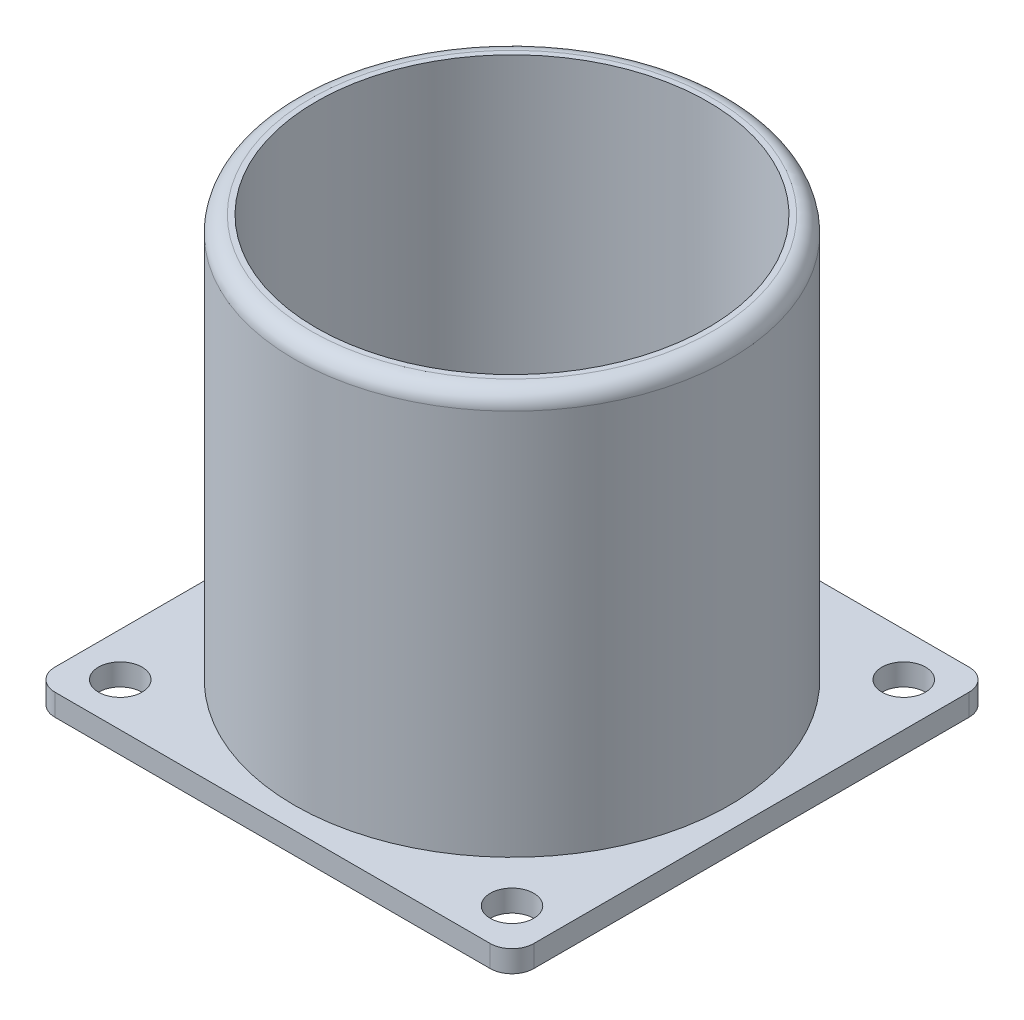
SolidWorks part; units mm, degrees
ref_plane "Plano frontal" through (0, 0, 0) normal (0, 0, 1) x (1, 0, 0)
ref_plane "Plano superior" through (0, 0, 0) normal (0, 1, 0) x (1, 0, 0)
ref_plane "Plano direito" through (0, 0, 0) normal (1, 0, 0) x (0, 0, -1)
sketch "Esboço1" plane through (0, 0, 0) normal (0, 1, 0) x (1, 0, 0)
  line L0 (0, 0) -> (0, 18) construction
  line L1 (-22, -22) -> (22, -22)
  line L2 (-22, -22) -> (-22, 22)
  line L3 (-22, 22) -> (22, 22)
  line L4 (22, -22) -> (22, 22)
  line L5 (-22, -22) -> (22, 22) construction
  line L6 (-22, 22) -> (22, -22) construction
  line L7 (-22, -18) -> (-18, -18) construction
  line L8 (-22, -18) -> (-22, -22) construction
  line L9 (-22, -22) -> (-18, -22) construction
  line L10 (-18, -18) -> (-18, -22) construction
  line L11 (-22, -18) -> (-18, -22) construction
  line L12 (-22, -22) -> (-18, -18) construction
  line L13 (0, 0) -> (8.3253, 0) construction
  line L14 (0.75, -17.9844) -> (0.75, 18)
  line L15 (-18, -18) -> (-16, -18) construction
  line L16 (-18, -18) -> (-18, -16) construction
  line L17 (-18, 18) -> (-6.75, 18) construction
  line L18 (18, -18) -> (18, 18) construction
  line L19 (-18, -18) -> (18, 18) construction
  line L20 (-18, 18) -> (18, -18) construction
  line L21 (-0.75, -17.9844) -> (-0.75, 18)
  line L22 (-0.75, 0) -> (-0.75, 22) construction
  line L23 (0.75, 0) -> (0.75, 22) construction
  line L24 (0.75, 18) -> (0.75, 22) construction
  line L25 (0, 17.7309) -> (0, 22) construction
  line L26 (0, 0) -> (0, 22) construction
  line L27 (-0.75, 18) -> (-0.75, 22) construction
  line L28 (0.75, -17.9844) -> (0.75, 18)
  line L29 (2.25, -17.9844) -> (2.25, 18)
  line L30 (2.25, -17.9844) -> (2.25, 18)
  line L31 (3.75, -17.9844) -> (3.75, 18)
  line L32 (3.75, -17.9844) -> (3.75, 18)
  line L33 (5.25, -17.9844) -> (5.25, 18)
  line L34 (5.25, -17.9844) -> (5.25, 18)
  line L35 (6.75, -17.9844) -> (6.75, 18)
  line L36 (6.75, -17.9844) -> (6.75, 18)
  line L37 (8.25, -17.9844) -> (8.25, 18)
  line L38 (8.25, -17.9844) -> (8.25, 18)
  line L39 (9.75, -17.9844) -> (9.75, 18)
  line L40 (9.75, -17.9844) -> (9.75, 18)
  line L41 (11.25, -17.9844) -> (11.25, 18)
  line L42 (11.25, -17.9844) -> (11.25, 18)
  line L43 (12.75, -17.9844) -> (12.75, 18)
  line L44 (12.75, -17.9844) -> (12.75, 18)
  line L45 (14.25, -17.9844) -> (14.25, 18)
  line L46 (14.25, -17.9844) -> (14.25, 18)
  line L47 (15.75, -17.9844) -> (15.75, 18)
  line L48 (15.75, -17.9844) -> (15.75, 18)
  line L49 (17.25, -17.9844) -> (17.25, 18)
  line L50 (-0.75, -17.9844) -> (0.75, -17.9844) construction
  line L51 (-0.75, 18) -> (0, 18) construction
  line L52 (0.75, 18) -> (2.25, 18) construction
  line L53 (0, 18) -> (0.75, 18) construction
  line L54 (-16, -18) -> (0, -18) construction
  line L55 (16, -18) -> (18, -18) construction
  line L56 (0, -18) -> (16, -18) construction
  line L57 (2.25, 18) -> (3.75, 18) construction
  line L58 (3.75, 18) -> (5.25, 18) construction
  line L59 (5.25, 18) -> (6.75, 18) construction
  line L60 (6.75, 18) -> (18, 18) construction
  line L61 (-17.25, -17.9844) -> (-17.25, 18)
  line L62 (-15.75, -17.9844) -> (-15.75, 18)
  line L63 (-14.25, -17.9844) -> (-14.25, 18)
  line L64 (-12.75, -17.9844) -> (-12.75, 18)
  line L65 (-11.25, -17.9844) -> (-11.25, 18)
  line L66 (-9.75, -17.9844) -> (-9.75, 18)
  line L67 (-8.25, -17.9844) -> (-8.25, 18)
  line L68 (-6.75, -17.9844) -> (-6.75, 18)
  line L69 (-5.25, -17.9844) -> (-5.25, 18)
  line L70 (-3.75, -17.9844) -> (-3.75, 18)
  line L71 (-2.25, -17.9844) -> (-2.25, 18)
  line L72 (-3.75, 18) -> (-2.25, 18) construction
  line L73 (-2.25, 18) -> (-0.75, 18) construction
  line L74 (-6.75, 18) -> (-5.25, 18) construction
  line L75 (-5.25, 18) -> (-3.75, 18) construction
  line L76 (-18, 0) -> (-18, 16) construction
  line L77 (-18, 16) -> (-18, 18) construction
  line L78 (-18, -16) -> (-18, 0) construction
  arc A0 (-0.75, 17.9844) -> (-2.25, 17.8588) centre (0, 0) ccw
  circle A1 centre (-18, -18) radius 2
  circle A2 centre (18, -18) radius 2
  circle A3 centre (18, 18) radius 2
  circle A4 centre (-18, 18) radius 2
  arc A5 (0, 18) -> (-0.75, 17.9844) centre (0, 0) ccw construction
  arc A6 (0.75, 17.9844) -> (0, 18) centre (0, 0) ccw construction
  arc A7 (-0.75, -17.9844) -> (0, -18) centre (0, 0) ccw construction
  arc A8 (0, -18) -> (2.25, -17.8588) centre (0, 0) ccw
  arc A9 (2.25, -17.8588) -> (3.75, -17.605) centre (0, 0) ccw construction
  arc A10 (3.75, -17.605) -> (5.25, -17.2174) centre (0, 0) ccw
  arc A11 (3.75, 17.605) -> (2.25, 17.8588) centre (0, 0) ccw construction
  arc A12 (2.25, 17.8588) -> (0.75, 17.9844) centre (0, 0) ccw
  arc A13 (6.75, 16.6864) -> (5.25, 17.2174) centre (0, 0) ccw construction
  arc A14 (5.25, 17.2174) -> (3.75, 17.605) centre (0, 0) ccw
  arc A15 (5.25, -17.2174) -> (6.75, -16.6864) centre (0, 0) ccw construction
  arc A16 (6.75, -16.6864) -> (8.25, -15.998) centre (0, 0) ccw
  arc A17 (8.25, -15.998) -> (9.75, -15.1307) centre (0, 0) ccw construction
  arc A18 (9.75, -15.1307) -> (11.25, -14.0512) centre (0, 0) ccw
  arc A19 (9.75, 15.1307) -> (8.25, 15.998) centre (0, 0) ccw construction
  arc A20 (8.25, 15.998) -> (6.75, 16.6864) centre (0, 0) ccw
  arc A21 (12.7279, 12.7279) -> (11.25, 14.0512) centre (0, 0) ccw construction
  arc A22 (11.25, 14.0512) -> (9.75, 15.1307) centre (0, 0) ccw
  arc A23 (11.25, -14.0512) -> (12.7279, -12.7279) centre (0, 0) ccw construction
  arc A24 (12.7279, -12.7279) -> (14.25, -10.9972) centre (0, 0) ccw
  arc A25 (14.25, -10.9972) -> (15.75, -8.7142) centre (0, 0) ccw construction
  arc A26 (15.75, -8.7142) -> (17.25, -5.1417) centre (0, 0) ccw
  arc A27 (15.75, 8.7142) -> (14.25, 10.9972) centre (0, 0) ccw construction
  arc A28 (14.25, 10.9972) -> (12.7279, 12.7279) centre (0, 0) ccw
  arc A29 (18, 0) -> (17.25, 5.1417) centre (0, 0) ccw construction
  arc A30 (17.25, 5.1417) -> (15.75, 8.7142) centre (0, 0) ccw
  arc A31 (17.25, -5.1417) -> (18, 0) centre (0, 0) ccw construction
  arc A32 (-2.25, 17.8588) -> (-3.75, 17.605) centre (0, 0) ccw construction
  arc A33 (-3.75, 17.605) -> (-5.25, 17.2174) centre (0, 0) ccw
  arc A34 (-3.75, -17.605) -> (-2.25, -17.8588) centre (0, 0) ccw construction
  arc A35 (-2.25, -17.8588) -> (-0.75, -17.9844) centre (0, 0) ccw
  arc A36 (-6.75, -16.6864) -> (-5.25, -17.2174) centre (0, 0) ccw construction
  arc A37 (-5.25, -17.2174) -> (-3.75, -17.605) centre (0, 0) ccw
  arc A38 (-5.25, 17.2174) -> (-6.75, 16.6864) centre (0, 0) ccw construction
  arc A39 (-6.75, 16.6864) -> (-8.25, 15.998) centre (0, 0) ccw
  arc A40 (-8.25, 15.998) -> (-9.75, 15.1307) centre (0, 0) ccw construction
  arc A41 (-9.75, 15.1307) -> (-11.25, 14.0512) centre (0, 0) ccw
  arc A42 (-9.75, -15.1307) -> (-8.25, -15.998) centre (0, 0) ccw construction
  arc A43 (-8.25, -15.998) -> (-6.75, -16.6864) centre (0, 0) ccw
  arc A44 (-12.7279, -12.7279) -> (-11.25, -14.0512) centre (0, 0) ccw construction
  arc A45 (-11.25, -14.0512) -> (-9.75, -15.1307) centre (0, 0) ccw
  arc A46 (-11.25, 14.0512) -> (-12.7279, 12.7279) centre (0, 0) ccw construction
  arc A47 (-12.7279, 12.7279) -> (-14.25, 10.9972) centre (0, 0) ccw
  arc A48 (-14.25, 10.9972) -> (-15.75, 8.7142) centre (0, 0) ccw construction
  arc A49 (-15.75, 8.7142) -> (-17.25, 5.1417) centre (0, 0) ccw
  arc A50 (-15.75, -8.7142) -> (-14.25, -10.9972) centre (0, 0) ccw construction
  arc A51 (-14.25, -10.9972) -> (-12.7279, -12.7279) centre (0, 0) ccw
  arc A52 (-17.25, 5.1417) -> (-18, 0) centre (0, 0) ccw construction
  arc A53 (-17.25, -5.1417) -> (-15.75, -8.7142) centre (0, 0) ccw
  arc A54 (-18, 0) -> (-17.25, -5.1417) centre (0, 0) ccw construction
  point P7 (-20, -20)
  dimension "D1" = 36
  dimension "D4" = 4
  dimension "D2" = 44
  dimension "D3" = 4
  dimension "D8" = 1.5
  dimension "D5" = 0.75
  dimension "D6" = 0.75
  dimension "D7" = 12
extrude "Ressalto-extrusão1" add sketch "Esboço1" along normal blind 2
ref_plane "Plano1" through (0, 2, 0) normal (0, 1, 0) x (1, 0, 0)
sketch "Esboço3" plane through (0, 2, 0) normal (0, 1, 0) x (1, 0, 0)
  circle A0 centre (0, 0) radius 18
  arc A1 (5.25, 17.2174) -> (3.75, 17.605) centre (0, 0) ccw construction
  circle A2 centre (0, 0) radius 20
  dimension "D1" = 2
extrude "Ressalto-extrusão3" add sketch "Esboço3" along normal blind 37
fillet "Filete3" radius 1.5 1 edges at (0, 39, 20)
fillet "Filete4" radius 2 4 edges at (-22, 1, -22) (-22, 1, 22) (22, 1, 22) (22, 1, -22)
equation "\"D2@Esboço1\"=\"D1@Esboço1\"+8"
